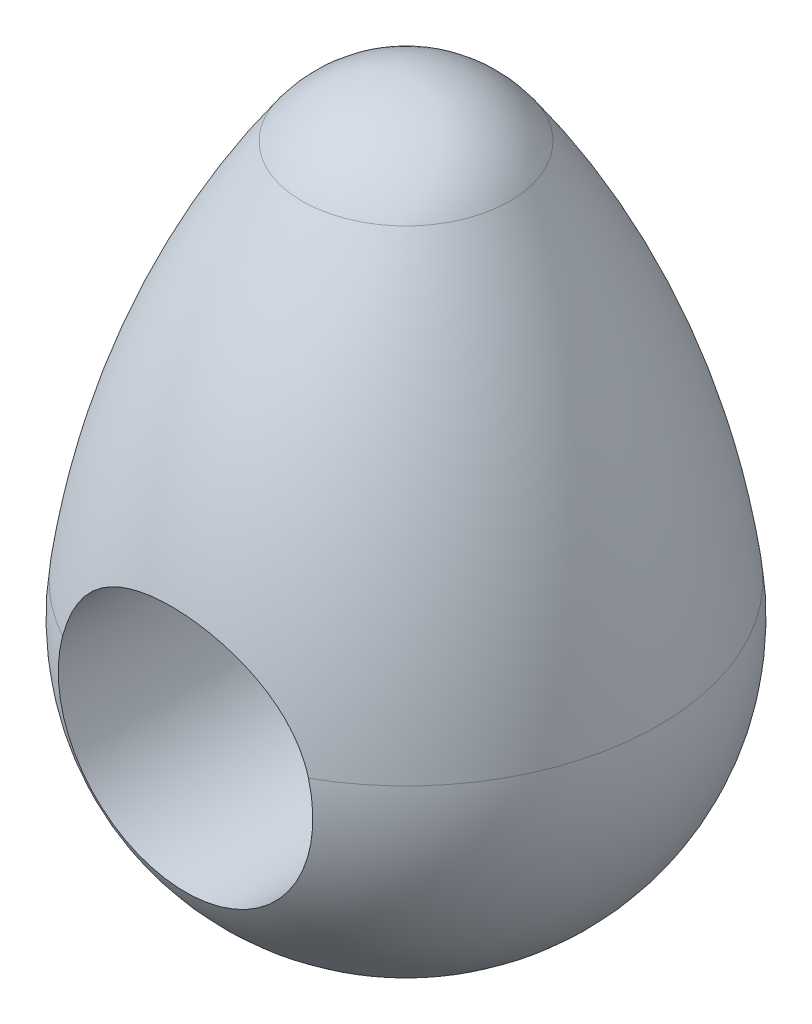
SolidWorks part; units mm, degrees
ref_plane "Front Plane" through (0, 0, 0) normal (0, 0, 1) x (1, 0, 0)
ref_plane "Top Plane" through (0, 0, 0) normal (0, 1, 0) x (1, 0, 0)
ref_plane "Right Plane" through (0, 0, 0) normal (1, 0, 0) x (0, 0, -1)
sketch "Sketch2" plane through (0, 0, 0) normal (0, 0, 1) x (1, 0, 0)
  line L0 (0, 50.8) -> (0, 0) construction
  line L1 (0, 69.85) -> (0, -38.1)
  arc A0 (15.5562, 61.7958) -> (-15.5562, 61.7958) centre (0, 50.8) ccw
  arc A1 (-37.7794, 4.9326) -> (37.7794, 4.9326) centre (0, 0) ccw
  arc A2 (-15.5562, 61.7958) -> (-37.7794, 4.9326) centre (88.1518, -11.5094) ccw
  arc A3 (15.5562, 61.7958) -> (37.7794, 4.9326) centre (-88.1518, -11.5094) cw
  dimension "D1" = 38.1
  dimension "D3" = 76.2
  dimension "D4" = 127
  dimension "D2" = 50.8
revolve "Revolve1" add sketch "Sketch2" angle 360 about L0
sketch "Sketch3" plane through (0, 0, 0) normal (0, 0, 1) x (1, 0, 0)
  arc A0 (15.5562, 61.7958) -> (-15.5562, 61.7958) centre (0, 50.8) ccw construction
  arc A1 (-15.5562, 61.7958) -> (-37.7794, 4.9326) centre (88.1518, -11.5094) ccw construction
  arc A2 (37.7794, 4.9326) -> (15.5562, 61.7958) centre (-88.1518, -11.5094) ccw construction
  arc A3 (-37.7794, 4.9326) -> (37.7794, 4.9326) centre (0, 0) ccw construction
  arc A4 (15.5562, 61.7958) -> (-15.5562, 61.7958) centre (0, 50.8) ccw
  arc A5 (-15.5562, 61.7958) -> (-37.7794, 4.9326) centre (88.1518, -11.5094) ccw
  arc A6 (37.7794, 4.9326) -> (15.5562, 61.7958) centre (-88.1518, -11.5094) ccw
  arc A7 (-37.7794, 4.9326) -> (37.7794, 4.9326) centre (0, 0) ccw
  circle A8 centre (0, 0) radius 19.05
  dimension "D1" = 38.1
extrude "Cut-Extrude1" cut sketch "Sketch3" along normal through all both and the other way through all contours A8 | A4 A5 A7 A6
